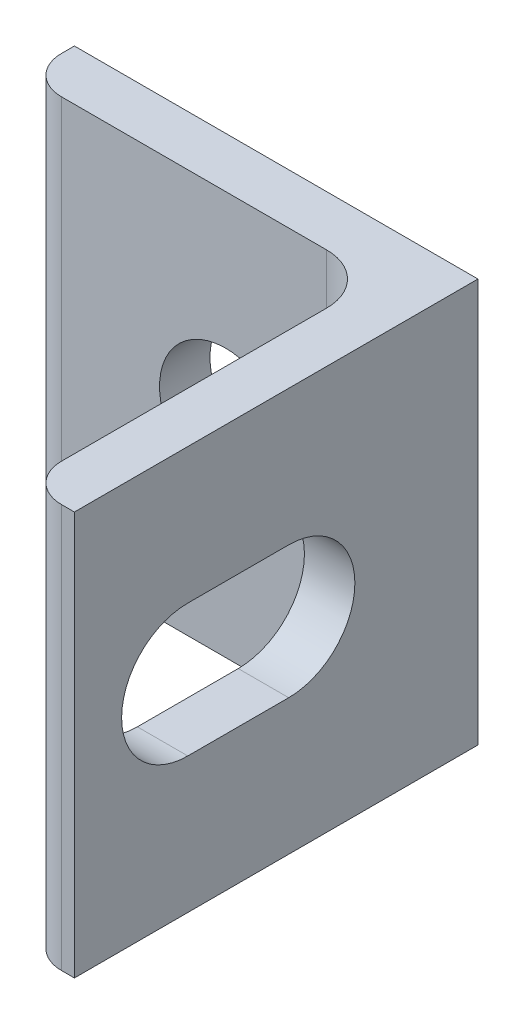
SolidWorks part; units mm, degrees
ref_plane "Front Plane" through (0, 0, 0) normal (0, 0, 1) x (1, 0, 0)
ref_plane "Top Plane" through (0, 0, 0) normal (0, 1, 0) x (1, 0, 0)
ref_plane "Right Plane" through (0, 0, 0) normal (1, 0, 0) x (0, 0, -1)
sketch "Sketch1" plane through (0, 0, 0) normal (1, 0, 0) x (0, 0, -1)
  line L0 (-25.4, -25.4) -> (0, -25.4)
  line L1 (0, -25.4) -> (0, 0)
  line L2 (0, 0) -> (-25.4, 0)
  line L3 (-25.4, 0) -> (-25.4, -25.4)
extrude "Boss-Extrude1" add sketch "Sketch1" against normal blind 25.4
sketch "Sketch2" plane through (0, -25.4, 0) normal (0, -1, 0) x (1, 0, 0)
  line L0 (-25.4, 3.175) -> (-3.175, 3.175)
  line L1 (-3.175, 3.175) -> (-3.175, 25.4)
  line L2 (-3.175, 25.4) -> (-25.4, 25.4)
  line L3 (-25.4, 25.4) -> (-25.4, 3.175)
extrude "Cut-Extrude1" cut sketch "Sketch2" against normal through all
sketch "Sketch3" plane through (0, 0, 0) normal (1, 0, 0) x (0, 0, -1)
  line L0 (-18.2626, -16.8656) -> (-11.9126, -16.8656)
  line L1 (-11.9126, -8.5344) -> (-18.2626, -8.5344)
  arc A0 (-18.2626, -8.5344) -> (-18.2626, -16.8656) centre (-18.2626, -12.7) ccw
  arc A1 (-11.9126, -16.8656) -> (-11.9126, -8.5344) centre (-11.9126, -12.7) ccw
extrude "Cut-Extrude2" cut sketch "Sketch3" against normal through all
hole_wizard "Hole1" positions "Sketch5" profile "Sketch4" legacy
sketch "Sketch5" plane through (0, 0, 3.175) normal (0, 0, 1) x (1, 0, 0)
  point P0 (-12.7, -12.7)
sketch "Sketch4" plane through (-12.7, -12.7, 3.175) normal (1, 0, 0) x (0, -1, 0)
  line L0 (0, 0) -> (0, 3.175)
  line L1 (0, 3.175) -> (4.1656, 3.175)
  line L2 (4.1656, 3.175) -> (4.1656, 0)
  line L3 (4.1656, 0) -> (0, 0)
  line L4 (0, 110) -> (0, -10) construction
  dimension "Diameter" = 8.3312
  dimension "Depth" = 3.175
fillet "Fillet1" radius 2.3622 2 edges at (-25.4, -12.7, 3.175) (-3.175, -12.7, 25.4)
fillet "Fillet2" radius 3.175 1 edges at (-3.175, -12.7, 3.175)
